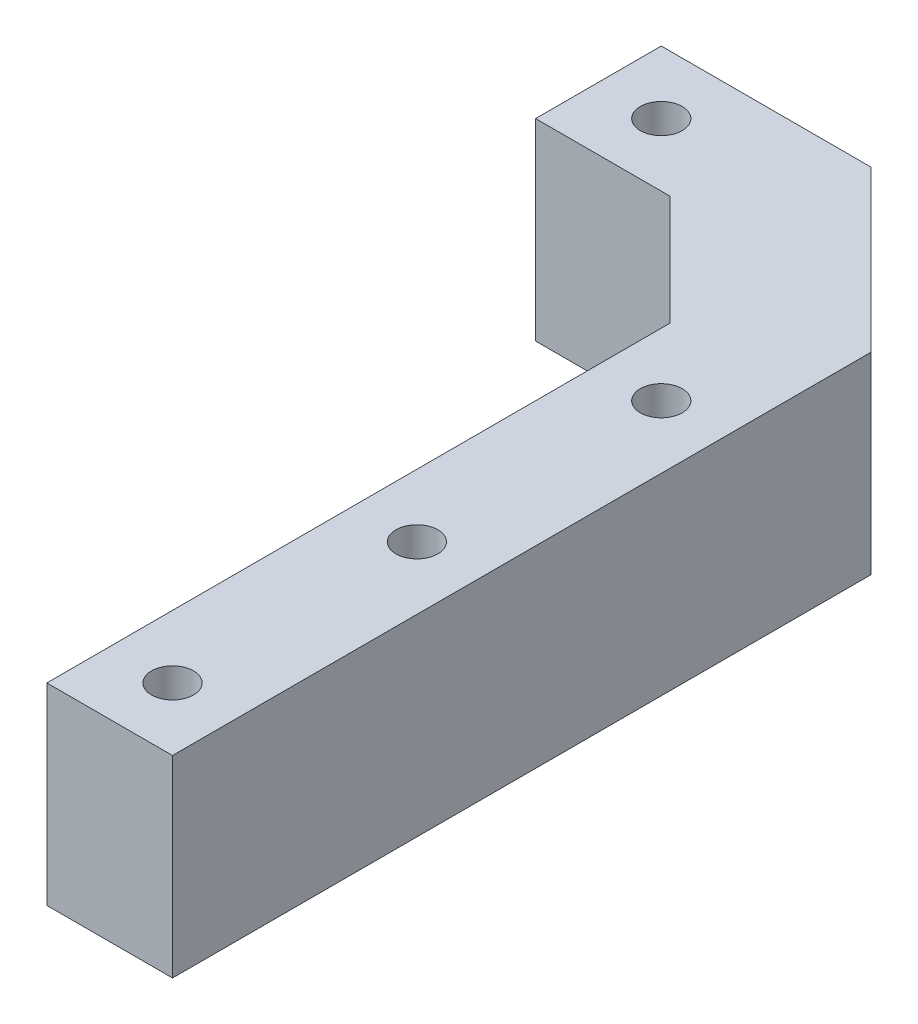
SolidWorks part; units mm, degrees
ref_plane "前视基准面" through (0, 0, 0) normal (0, 0, 1) x (1, 0, 0)
ref_plane "上视基准面" through (0, 0, 0) normal (0, 1, 0) x (1, 0, 0)
ref_plane "右视基准面" through (0, 0, 0) normal (1, 0, 0) x (0, 0, -1)
other "Configuration Table"
sketch "草图2" plane through (0, 0, 0) normal (0, 1, 0) x (1, 0, 0)
  line L0 (0, -20.8431) -> (0, -49.1569) construction
  line L1 (-35, 35) -> (35, 35) construction
  line L2 (-35, 35) -> (-35, -35) construction
  line L3 (-35, -35) -> (35, -35) construction
  line L4 (35, 35) -> (35, -35) construction
  line L5 (-35, 35) -> (35, -35) construction
  line L6 (-35, -35) -> (35, 35) construction
  line L7 (-49.9747, 0) -> (-20.0253, 0) construction
  line L9 (-37.5, -15) -> (-37.5, -20) construction
  line L13 (-15, -37.5) -> (-15, -25.2969) construction
  line L14 (-15, -25.2969) -> (-25.2969, -15) construction
  line L17 (-37.5, -20) -> (-29.054, -20) construction
  line L18 (-29.054, -20) -> (-20, -29.054) construction
  line L19 (-20, -29.054) -> (-20, -37.5) construction
  line L25 (-37.5, -15) -> (-25.2969, -15) construction
  line L26 (-20, -37.5) -> (-20, -72.5) construction
  line L27 (-20, -72.5) -> (-15, -72.5) construction
  line L28 (-15, -72.5) -> (-15, -37.5) construction
  line L29 (-39.5, -13) -> (-39.5, -22)
  line L30 (-39.5, -22) -> (-29.8824, -22)
  line L31 (-29.8824, -22) -> (-22, -29.8824)
  line L32 (-22, -29.8824) -> (-22, -37.5)
  line L33 (-22, -37.5) -> (-22, -74.5)
  line L34 (-22, -74.5) -> (-13, -74.5)
  line L35 (-13, -74.5) -> (-13, -37.5)
  line L36 (-13, -37.5) -> (-13, -24.4685)
  line L37 (-13, -24.4685) -> (-24.4685, -13)
  line L38 (-39.5, -13) -> (-24.4685, -13)
  circle A0 centre (-35, -17.5) radius 1.5
  circle A1 centre (-17.5, -35) radius 1.5
  circle A3 centre (-17.5, -52.5) radius 1.5
  circle A4 centre (-17.5, -70) radius 1.5
  point P0 (0, 0)
  point P9 (0, -35)
  point P12 (-35, 0)
  dimension "D3" = 3
  dimension "D4" = 17.5
  dimension "D5" = 17.5
  dimension "D6" = 3
  dimension "D1" = 70
  dimension "D2" = 70
  dimension "D7" = 2.5
  dimension "D8" = 17.5
  dimension "D9" = 2
  dimension "D10" = 2.5
  dimension "D11" = 2.5
  dimension "D12" = 2
extrude "凸台-拉伸1" add sketch "草图2" along normal blind 13.8
